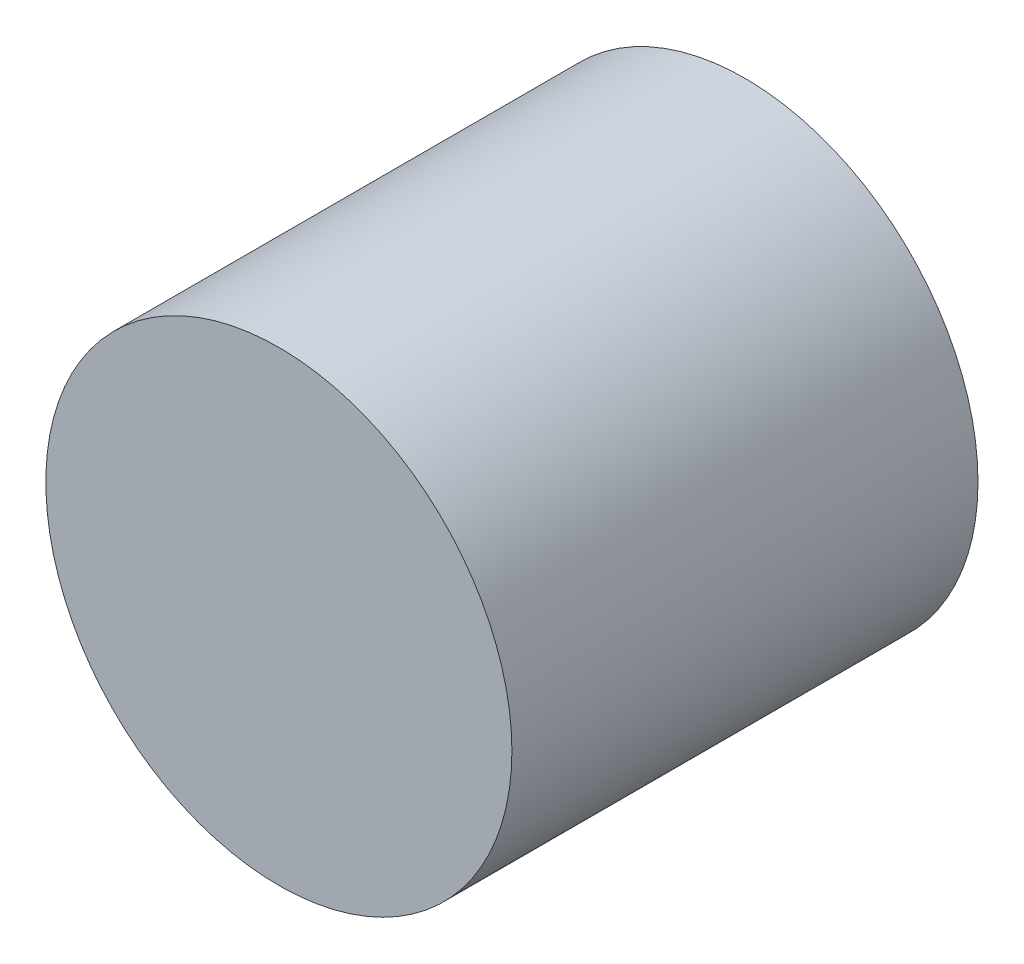
SolidWorks part; units mm, degrees
ref_plane "前视基准面" through (0, 0, 0) normal (0, 0, 1) x (1, 0, 0)
ref_plane "上视基准面" through (0, 0, 0) normal (0, 1, 0) x (1, 0, 0)
ref_plane "右视基准面" through (0, 0, 0) normal (1, 0, 0) x (0, 0, -1)
other "Configuration Table"
sketch "草图1" plane through (0, 0, 0) normal (0, 0, 1) x (1, 0, 0)
  circle A0 centre (0, 0) radius 6
  dimension "D1" = 12
extrude "凸台-拉伸1" add sketch "草图1" along normal mid plane 12
